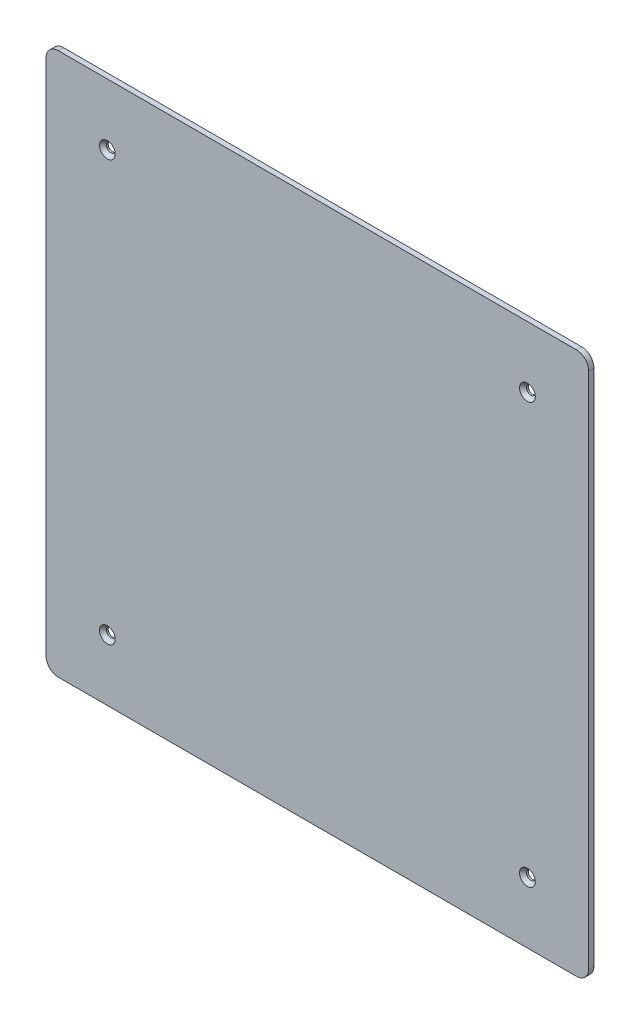
SolidWorks part; units mm, degrees
ref_plane "Front Plane" through (0, 0, 0) normal (1, 0, 0) x (0, 1, 0)
ref_plane "Top Plane" through (0, 0, 0) normal (0, 0, 1) x (0, 1, 0)
ref_plane "Right Plane" through (0, 0, 0) normal (0, 1, 0) x (-1, 0, 0)
sketch "Sketch1" plane through (0, 0, 0) normal (0, 0, 1) x (0, 1, 0)
  line L1 (-155, 155) -> (155, 155)
  line L2 (-155, 155) -> (-155, -155)
  line L3 (-155, -155) -> (155, -155)
  line L4 (155, 155) -> (155, -155)
  line L5 (-155, 155) -> (155, -155) construction
  line L6 (-155, -155) -> (155, 155) construction
  point P0 (0, 0)
  dimension "D1" = 310
  dimension "D2" = 310
extrude "Boss-Extrude1" add sketch "Sketch1" along normal blind 3
fillet "Fillet1" radius 7 4 edges at (155, -155, 1.5) (-155, -155, 1.5) (-155, 155, 1.5) (155, 155, 1.5)
sketch "Sketch2" plane through (0, 0, 3) normal (0, 0, 1) x (1, 0, 0)
  line L1 (-120, 120) -> (120, 120) construction
  line L2 (-120, 120) -> (-120, -120) construction
  line L3 (-120, -120) -> (120, -120) construction
  line L4 (120, 120) -> (120, -120) construction
  line L5 (-120, 120) -> (120, -120) construction
  line L6 (-120, -120) -> (120, 120) construction
  circle A0 centre (-120, 120) radius 2.5
  circle A1 centre (120, 120) radius 2.5
  circle A2 centre (120, -120) radius 2.5
  circle A3 centre (-120, -120) radius 2.5
  point P0 (0, 0)
  dimension "D3" = 5
  dimension "D1" = 240
  dimension "D2" = 240
extrude "Cut-Extrude1" cut sketch "Sketch2" against normal through all
chamfer "Chamfer1" distance 2 angle 45 4 edges at (-117.5, -120, 3) (122.5, -120, 3) (122.5, 120, 3) (-117.5, 120, 3)
